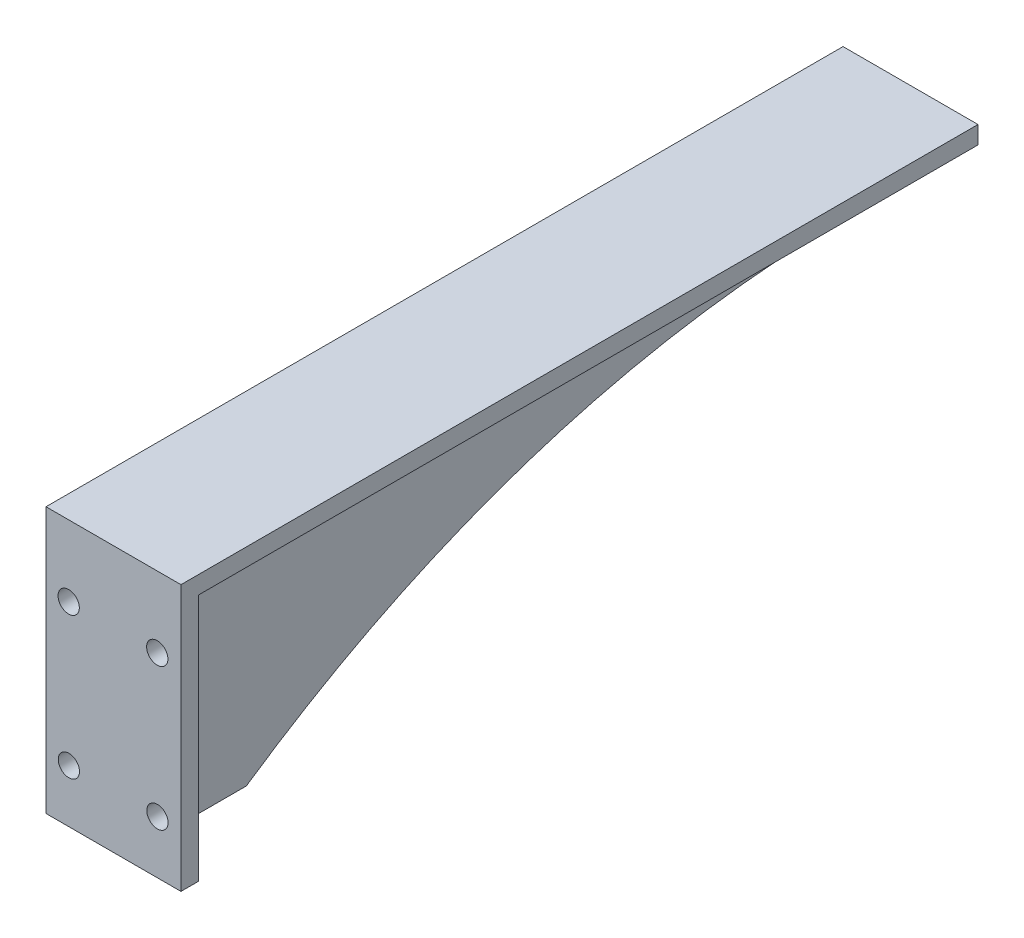
SolidWorks part; units mm, degrees
material "Aleación 1060"
ref_plane "Alzado" through (0, 0, 0) normal (0, 0, 1) x (1, 0, 0)
ref_plane "Planta" through (0, 0, 0) normal (0, 1, 0) x (1, 0, 0)
ref_plane "Vista lateral" through (0, 0, 0) normal (1, 0, 0) x (0, 0, -1)
sketch "Croquis1" plane through (0, 0, 0) normal (1, 0, 0) x (0, 0, -1)
  line L1 (0, 0) -> (220, 0)
  line L2 (0, 0) -> (0, -70)
  line L3 (0, -70) -> (30, -70)
  line L4 (220, 0) -> (220, -16)
  spline S0 degree 2 poles (30, -70) (116.6102, -10.8351) (220, -16) knots 0 0 0 1 1 1
  point P1 (112.2913, -25.2459)
  point P7 (133.1567, -23.6958)
  dimension "D1" = 220
  dimension "D2" = 70
  dimension "D3" = 16
  dimension "D4" = 30
extrude "Saliente-Extruir1" add sketch "Croquis1" along normal mid plane 5
sketch "Croquis3" plane through (0, 0, 0) normal (0, 1, 0) x (1, 0, 0)
  line L0 (-19.05, 0) -> (19.05, 0)
  line L1 (2.5, 220) -> (-2.5, 220) construction
  line L2 (19.05, 0) -> (19.05, 220)
  line L3 (19.05, 220) -> (-19.05, 220)
  line L4 (-19.05, 0) -> (-19.05, 220)
  line L5 (0, 0) -> (-19.05, 220) construction
  line L6 (19.05, 220) -> (0, 0) construction
  line L7 (2.5, 220) -> (-2.5, 220) construction
  point P0 (0, 0)
  point P9 (0, 220)
  point P10 (0, 220)
  dimension "D1" = 38.1
extrude "Saliente-Extruir2" add sketch "Croquis3" along normal blind 5
sketch "Croquis4" plane through (0, 0, 0) normal (0, 0, 1) x (1, 0, 0)
  line L0 (2.5, -70) -> (-2.5, -70) construction
  line L1 (-19.05, 5) -> (19.05, 5)
  line L2 (-19.05, 5) -> (-19.05, -70)
  line L3 (-19.05, -70) -> (19.05, -70)
  line L4 (19.05, 5) -> (19.05, -70)
  point P5 (0, -70)
  point P8 (0, -70)
extrude "Saliente-Extruir3" add sketch "Croquis4" along normal blind 5
sketch "Croquis5" plane through (0, 0, 5) normal (0, 0, 1) x (1, 0, 0)
  circle A0 centre (-12.6457, -15.0363) radius 3
  circle A1 centre (12.3543, -15.0363) radius 3
  circle A2 centre (-12.595, -55.0363) radius 3
  circle A3 centre (12.405, -55.0363) radius 3
  point P8 (0, 0)
  point P9 (0, 0)
  point P10 (-12.6457, -55.0363)
  dimension "D1" = 6
  dimension "D2" = 6
  dimension "D3" = 6
  dimension "D4" = 6
  dimension "D5" = 25
  dimension "D6" = 25
  dimension "D7" = 40
extrude "Cortar-Extruir1" cut sketch "Croquis5" against normal blind 5
